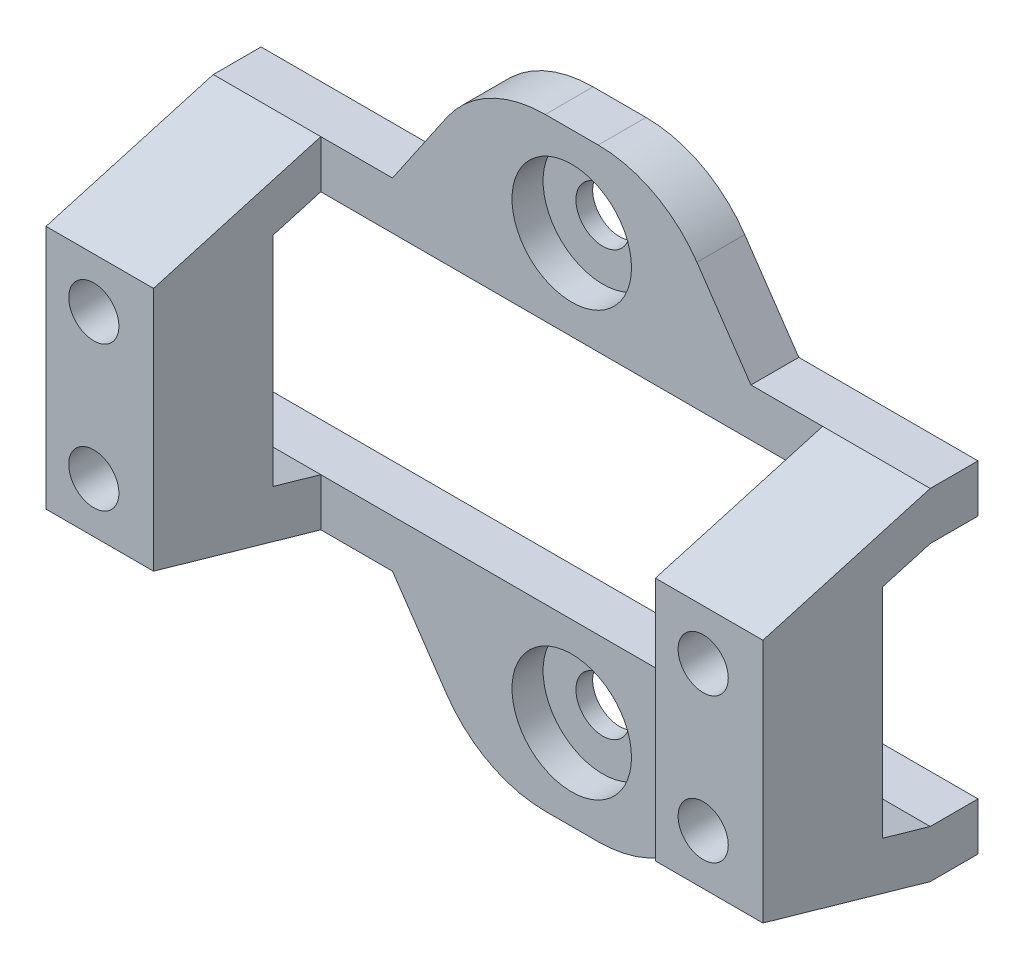
SolidWorks part; units mm, degrees
material "ABS"
ref_plane "Piano frontale" through (0, 0, 0) normal (0, 0, 1) x (1, 0, 0)
ref_plane "Piano superiore" through (0, 0, 0) normal (0, 1, 0) x (1, 0, 0)
ref_plane "Piano destro" through (0, 0, 0) normal (1, 0, 0) x (0, 0, -1)
sketch "Schizzo3" plane through (0, 0, 0) normal (0, 0, 1) x (1, 0, 0)
  line L0 (-30, 10.25) -> (30, 10.25)
  line L1 (30, 10.25) -> (30, -10.25) construction
  line L2 (30, -10.25) -> (-30, -10.25)
  line L3 (-30, -10.25) -> (-30, -14.25)
  line L4 (-30, -14.25) -> (-15, -14.25)
  line L5 (30, -14.25) -> (30, -10.25)
  line L6 (30, 10.25) -> (30, 14.25)
  line L7 (30, 14.25) -> (15, 14.25)
  line L8 (-30, 14.25) -> (-30, 10.25)
  line L9 (-30, 10.25) -> (-30, -10.25) construction
  line L10 (-30, 0) -> (30, 0) construction
  line L11 (0, -25.25) -> (0, 25.25) construction
  line L12 (-7.5, 25.25) -> (7.5, 25.25)
  line L13 (7.5, 25.25) -> (15, 14.25)
  line L14 (-7.5, 25.25) -> (-15, 14.25)
  line L15 (-15, -14.25) -> (-7.5, -25.25)
  line L16 (-7.5, -25.25) -> (7.5, -25.25)
  line L17 (7.5, -25.25) -> (15, -14.25)
  line L18 (0, -25.25) -> (0, 25.25) construction
  line L19 (15, -14.25) -> (30, -14.25)
  line L20 (-15, 14.25) -> (-30, 14.25)
  point P12 (0, 0)
  dimension "D1" = 4
  dimension "D2" = 20.5
  dimension "D3" = 60
  dimension "D4" = 11
  dimension "D5" = 11
  dimension "D6" = 15
  dimension "D7" = 15
  dimension "D8" = 30
extrude "Estrusione-Estrusione1" add sketch "Schizzo3" along normal blind 4
sketch "Schizzo4" plane through (-30, 0, 0) normal (-1, 0, 0) x (0, 0, 1)
  line L0 (4, 14.25) -> (18, 10.25)
  line L1 (18, 10.25) -> (18, -10.25)
  line L2 (18, -10.25) -> (4, -14.25)
  line L3 (4, -14.25) -> (4, -10.25)
  line L4 (4, -10.25) -> (8, -9.1071)
  line L5 (8, -9.1071) -> (8, 9.1071)
  line L6 (8, 9.1071) -> (4, 10.25)
  line L8 (0, 0) -> (18, 0)
  line L9 (0, 14.25) -> (0, 10.25) construction
  line L10 (4, 10.25) -> (18, 10.25) construction
  line M13 (4, 10.25) -> (4, 14.25)
  dimension "D1" = 10
  dimension "D2" = 18
extrude "Estrusione-Estrusione2" add sketch "Schizzo4" against normal blind 9 contours L10 L6 L5 L8 L1 | L8 L5 L4 L3 L2 L1 | L10 L0 M13
sketch "Schizzo5" plane through (30, 0, 0) normal (1, 0, 0) x (0, 0, -1)
  line L0 (-4, -14.25) -> (-18, -10.25)
  line L1 (-18, -10.25) -> (-18, 10.25)
  line L2 (-18, 10.25) -> (-4, 14.25)
  line L3 (-4, 14.25) -> (-4, 10.25)
  line L4 (-4, 10.25) -> (-8, 9.1071)
  line L5 (-8, 9.1071) -> (-8, -9.1071)
  line L6 (-8, -9.1071) -> (-4, -10.25)
  line L7 (-4, -10.25) -> (-4, -14.25)
  line L8 (-8, -9.1071) -> (-8, 9.1071) construction
  line L9 (-8, 9.1071) -> (-4, 10.25) construction
extrude "Estrusione-Estrusione3" add sketch "Schizzo5" against normal blind 9
fillet "Raccordo1" radius 10 4 edges at (7.5, -25.25, 2) (-7.5, -25.25, 2) (-7.5, 25.25, 2) (7.5, 25.25, 2)
sketch "Schizzo6" plane through (0, 0, 4) normal (0, 0, 1) x (1, 0, 0)
  line L0 (0, -17.75) -> (0, 17.75) construction
  line L2 (21, -10.25) -> (-21, -10.25) construction
  point P0 (0, 17.75)
  point P2 (0, -17.75)
  point P9 (0, 0)
  dimension "D1" = 7.5
hole_wizard "Foro lamato per Vite M4 a testa cilindrica piana-1" positions "Schizzo6" profile "Schizzo7" counterbore size "M4" standard "ISO"
sketch "Schizzo7" plane through (0, 17.75, 4) normal (1, 0, 0) x (0, -1, 0)
  line L0 (0, 0) -> (0, 35.3519)
  line L1 (0, 35.3519) -> (2.25, 34)
  line L2 (2.25, 34) -> (2.25, 2.6)
  line L3 (2.25, 2.6) -> (5, 2.6)
  line L4 (5, 2.6) -> (5, 0)
  line L5 (5, 0) -> (0, 0)
  line L10 (0, 35.3519) -> (-2.25, 34) construction
  line L11 (0, -6.35) -> (0, 107.95) construction
  dimension "Hole Dia." = 4.5
  dimension "Hole Depth" = 34
  dimension "C'Bore Dia." = 10
  dimension "C'Bore Depth" = 2.6
  dimension "Drill Angle" = 118
sketch "Schizzo9" plane through (0, 0, 18) normal (0, 0, 1) x (1, 0, 0)
  line L0 (-26, 6.05) -> (-26, -6.05) construction
  line L1 (-26, -6.05) -> (25, -6.05) construction
  line L2 (25, -6.05) -> (25, 6.05) construction
  line L3 (25, 6.05) -> (-26, 6.05) construction
  point P3 (-26, -6.05)
  point P6 (25, 6.05)
  point P9 (25, -6.05)
  point P52 (-26, 6.05)
  dimension "D1" = 12.1
  dimension "D2" = 51
  dimension "D3" = 6.05
  dimension "D5" = 25
hole_wizard "Foro per Vite M4-1" positions "Schizzo9" profile "Schizzo10" hole size "M4" standard "ISO"
sketch "Schizzo10" plane through (-26, -6.05, 18) normal (1, 0, 0) x (0, -1, 0)
  line L0 (0, 0) -> (0, 9.2618)
  line L1 (0, 9.2618) -> (2.1, 8)
  line L2 (2.1, 8) -> (2.1, 0)
  line L5 (2.1, 0) -> (0, 0)
  line L10 (0, 9.2618) -> (-2.1, 8) construction
  line L11 (0, -6.35) -> (0, 107.95) construction
  dimension "Hole Dia." = 4.2
  dimension "Hole Depth" = 8
  dimension "Drill Angle" = 118
